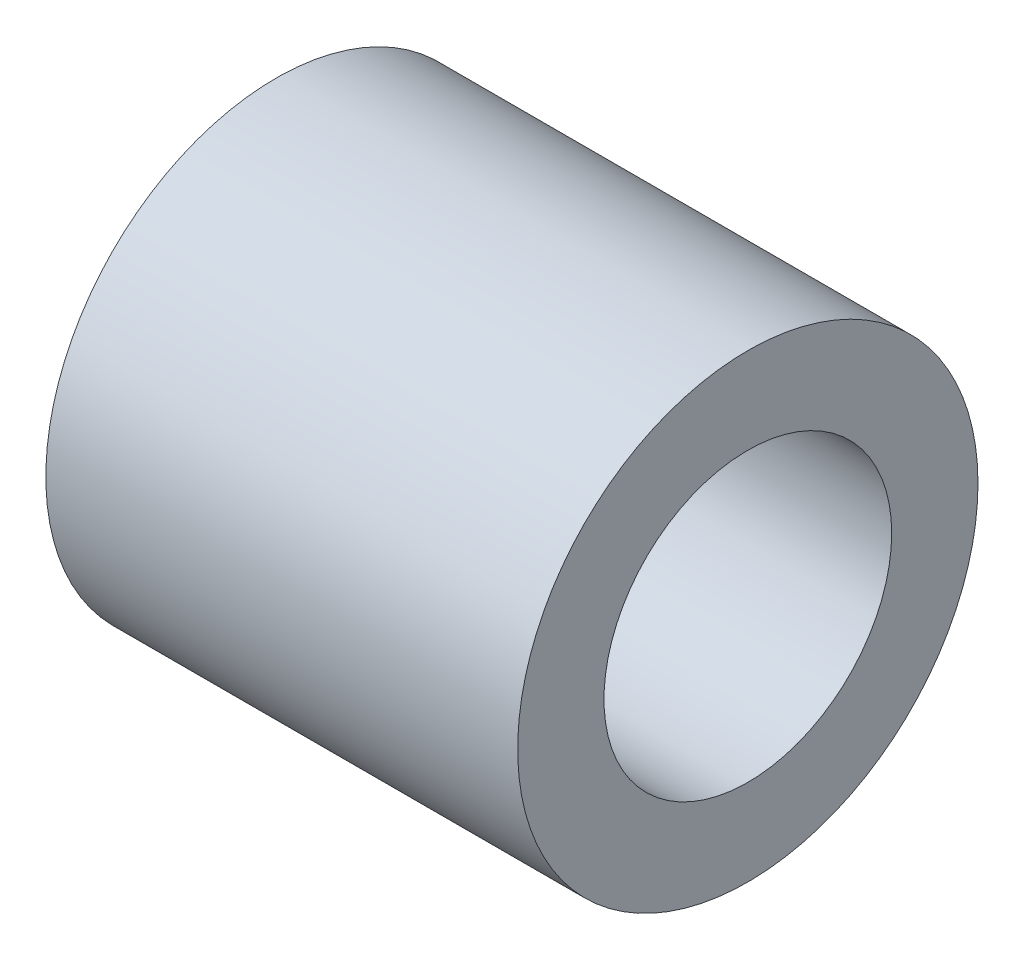
SolidWorks part; units mm, degrees
ref_plane "Front Plane" through (0, 0, 0) normal (0, 0, 1) x (1, 0, 0)
ref_plane "Top Plane" through (0, 0, 0) normal (0, 1, 0) x (1, 0, 0)
ref_plane "Right Plane" through (0, 0, 0) normal (1, 0, 0) x (0, 0, -1)
sketch "Sketch1" plane through (0, 0, 0) normal (1, 0, 0) x (0, 0, -1)
  circle A0 centre (0, 0) radius 2.5
  circle A1 centre (0, 0) radius 4
  dimension "D1" = 8
  dimension "D2" = 5
extrude "Boss-Extrude1" add sketch "Sketch1" along normal blind 8.2 contours A1 A0
